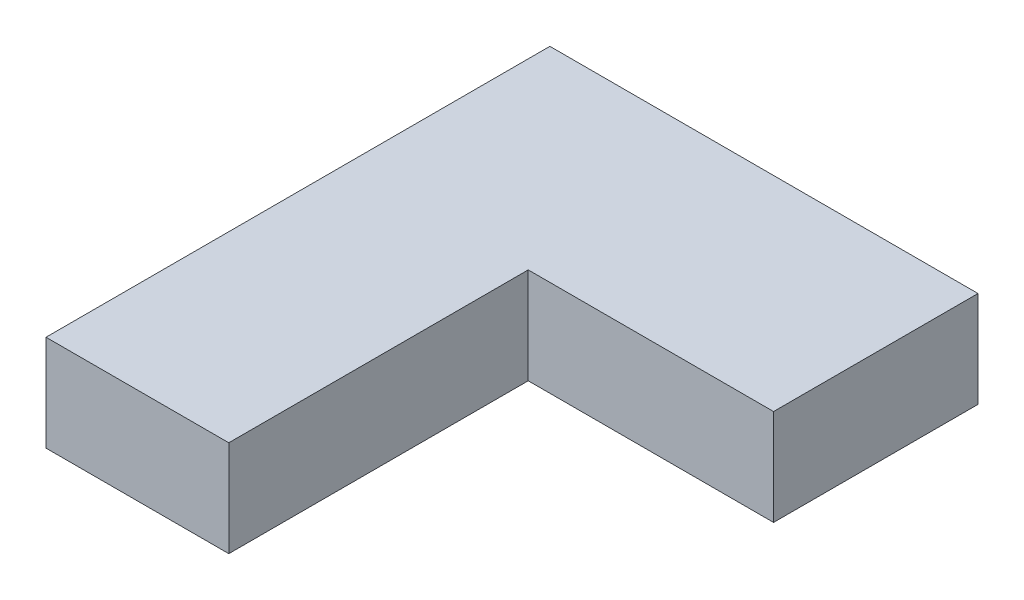
SolidWorks part; units mm, degrees
ref_plane "Front Plane" through (0, 0, 0) normal (0, 0, 1) x (1, 0, 0)
ref_plane "Top Plane" through (0, 0, 0) normal (0, 1, 0) x (1, 0, 0)
ref_plane "Right Plane" through (0, 0, 0) normal (1, 0, 0) x (0, 0, -1)
ref_plane "Plane1" through (0, 0, 0) normal (0, -1, 0) x (1, 0, 0)
sketch "Sketch1" plane through (0, 0, 0) normal (0, -1, 0) x (1, 0, 0)
  line L0 (44.569, -31.1733) -> (19.0295, -31.1733)
  line L1 (19.0295, -31.1733) -> (19.0295, 0)
  line L2 (19.0295, 0) -> (0, 0)
  line L3 (0, 0) -> (0, -52.4562)
  line L4 (0, -52.4562) -> (44.569, -52.4562)
  line L5 (44.569, -52.4562) -> (44.569, -31.1733)
extrude "Boss-Extrude1" add sketch "Sketch1" against normal blind 10
